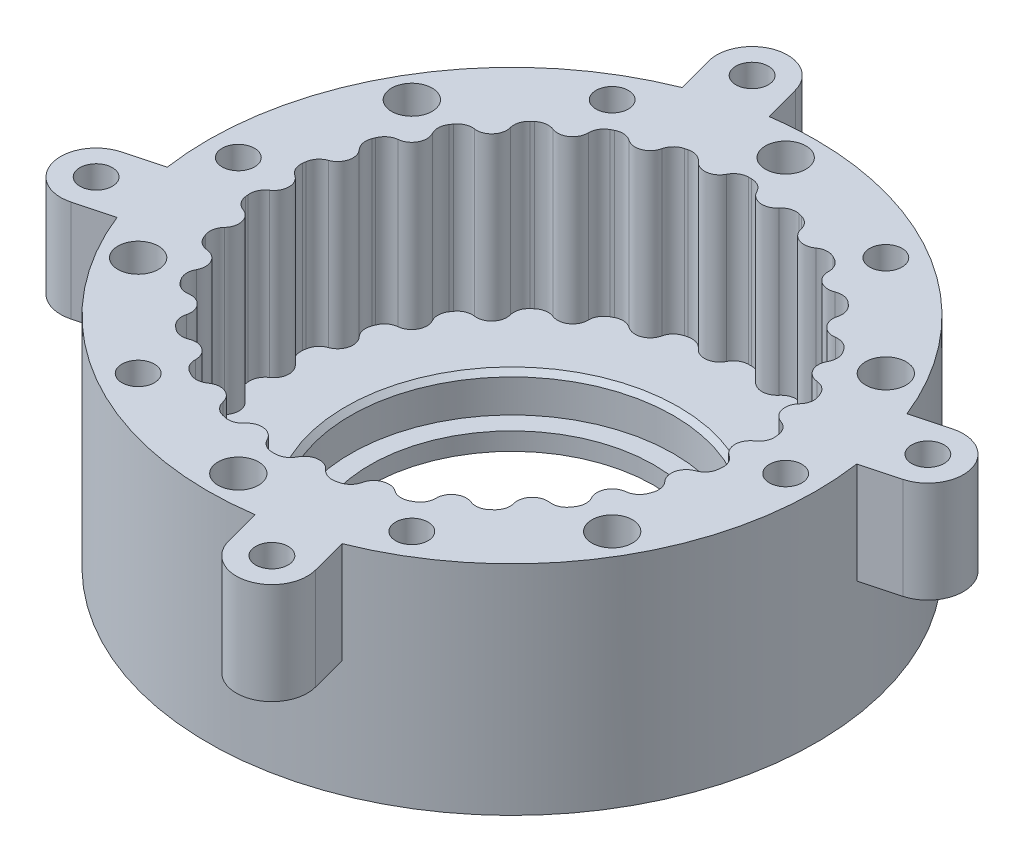
SolidWorks part; units mm, degrees
material "Like ABS"
ref_plane "Front Plane" through (0, 0, 0) normal (0, 0, 1) x (1, 0, 0)
ref_plane "Top Plane" through (0, 0, 0) normal (0, 1, 0) x (1, 0, 0)
ref_plane "Right Plane" through (0, 0, 0) normal (1, 0, 0) x (0, 0, -1)
sketch "Sketch1" plane through (0, 0, 0) normal (0, 1, 0) x (1, 0, 0)
  circle A0 centre (0, 0) radius 23.5
  circle A1 centre (0, 0) radius 30
  dimension "D1" = 47
  dimension "D2" = 60
extrude "Boss-Extrude4" add sketch "Sketch1" along normal blind 16
sketch "Sketch7" plane through (0, 0, 0) normal (0, -1, 0) x (1, 0, 0)
  circle A0 centre (0, 0) radius 30
  dimension "D1" = 60
extrude "Boss-Extrude6" add sketch "Sketch7" along normal blind 5.5
sketch "Sketch8" plane through (0, 16, 0) normal (0, 1, 0) x (1, 0, 0)
  line L0 (0, 0) -> (-27, 0) construction
  circle A0 centre (-27, 0) radius 1.6
  dimension "D2" = 3.2
  dimension "D1" = 27
extrude "Cut-Extrude4" cut sketch "Sketch8" against normal up to surface (21.5 mm away) up to face at (0, -5.5, -30)
pattern_circular "CirPattern19" count 12 over 360 about axis through (0, 0, 0) along (0, 1, 0) of "Cut-Extrude4"
sketch "Sketch9" plane through (0, -5.5, 0) normal (0, -1, 0) x (1, 0, 0)
  circle A0 centre (-27, 0) radius 2
  dimension "D1" = 4
extrude "Cut-Extrude5" cut sketch "Sketch9" against normal blind 4.5
pattern_circular "CirPattern21" count 6 over 360 about axis through (0, 0, 0) along (0, 1, 0) of "Cut-Extrude5"
sketch "Sketch10" plane through (0, 16, 0) normal (0, 1, 0) x (1, 0, 0)
  circle A0 centre (23.3827, 13.5) radius 2
  dimension "D1" = 4
extrude "Cut-Extrude6" cut sketch "Sketch10" against normal blind 4.5
pattern_circular "CirPattern22" count 6 over 360 about axis through (0, 0, 0) along (0, 1, 0) of "Cut-Extrude6"
sketch "Sketch12" plane through (0, 0, 0) normal (0, 1, 0) x (1, 0, 0)
  circle A0 centre (0, 0) radius 15.925
  dimension "D1" = 31.85
extrude "Cut-Extrude8" cut sketch "Sketch12" against normal blind 3.75
sketch "Sketch13" plane through (0, -3.75, 0) normal (0, 1, 0) x (1, 0, 0)
  circle A0 centre (0, 0) radius 14
  dimension "D1" = 28
extrude "Cut-Extrude9" cut sketch "Sketch13" against normal up to surface (1.75 mm away) up to face at (-11.7679, -5.5, -24.3827)
chamfer "Chamfer1" distance 0.5 angle 45 1 edges at (0, 0, 15.925)
sketch "Sketch15" plane through (0, 16, 0) normal (0, 1, 0) x (1, 0, 0)
  circle A0 centre (0, 0) radius 23.5 construction
  circle A1 centre (-23.5, 0) radius 1.5
  dimension "D1" = 47
  dimension "D2" = 3
extrude "Boss-Extrude9" add sketch "Sketch15" against normal up to surface (16 mm away) up to face at (0, 0, -16.425)
fillet "Fillet2" radius 1.5 2 edges at (-23.4521, 8, -1.4992) (-23.4521, 8, 1.4992)
pattern_circular "CirPattern28" count 26 over 360 about axis through (0, 0, 0) along (0, 1, 0) of "Fillet2", "Boss-Extrude9"
sketch "Sketch16" plane through (0, 16, 0) normal (0, 1, 0) x (1, 0, 0)
  line L0 (0, 5.2026) -> (0, 0) construction
  line L1 (0, 0) -> (-7.7646, 28.9778) construction
  line L2 (-7.7646, 28.9778) -> (-9.5763, 35.7393) construction
  line L3 (-12.0512, 31.4526) -> (-10.6734, 26.3109)
  line L4 (-10.6734, 26.3109) -> (-3.912, 28.1226)
  line L5 (-3.912, 28.1226) -> (-5.2897, 33.2644)
  arc A0 (-5.2897, 33.2644) -> (-12.0512, 31.4526) centre (-8.6704, 32.3585) ccw
  circle A1 centre (-8.6704, 32.3585) radius 1.6
  dimension "D4" = 3.2
  dimension "D1" = 15
  dimension "D2" = 30
  dimension "D3" = 7
extrude "Boss-Extrude10" add sketch "Sketch16" against normal blind 10
pattern_circular "CirPattern29" count 4 over 360 about axis through (0, 0, 0) along (0, 1, 0) of "Boss-Extrude10"
